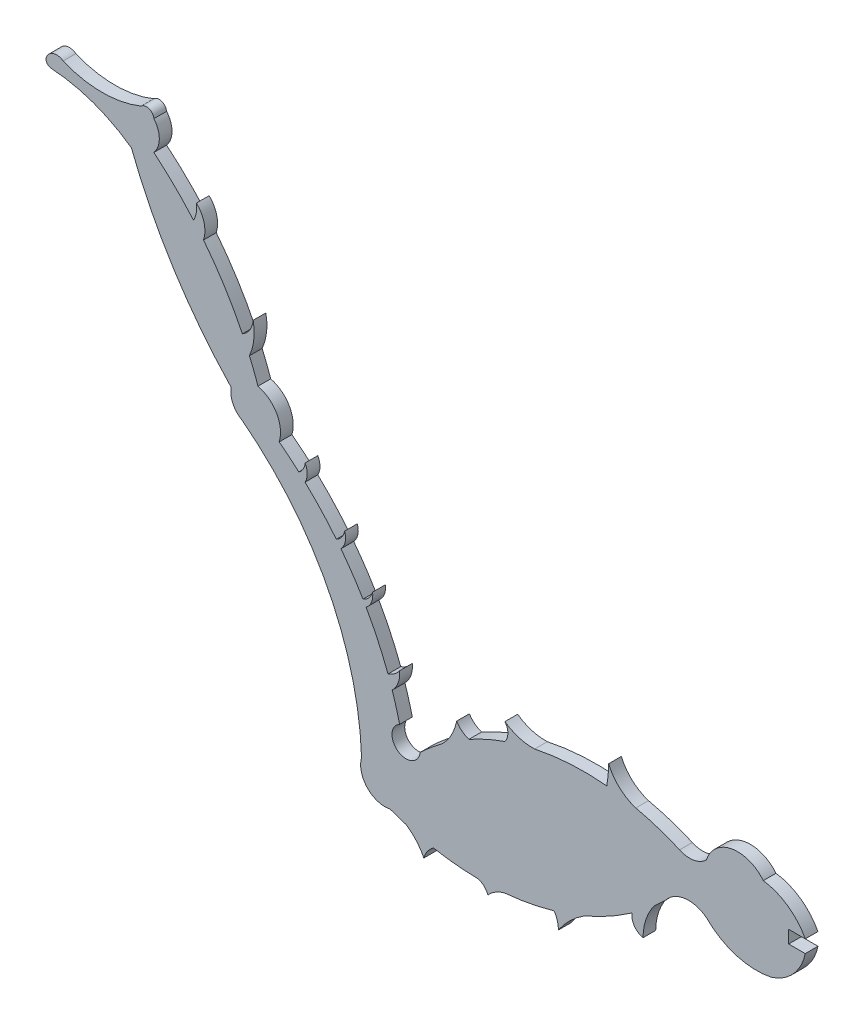
SolidWorks part; units mm, degrees
ref_plane "Front Plane" through (0, 0, 0) normal (0, 0, 1) x (1, 0, 0)
ref_plane "Top Plane" through (0, 0, 0) normal (0, 1, 0) x (1, 0, 0)
ref_plane "Right Plane" through (0, 0, 0) normal (1, 0, 0) x (0, 0, -1)
sketch "Sketch1" plane through (0, 0, 0) normal (0, 0, 1) x (1, 0, 0)
  line L0 (-80.679, -0.762) -> (-80.679, -1.524)
  line L1 (-80.679, -1.524) -> (-80.679, 0) construction
  line L2 (-80.679, -1.524) -> (-78.6924, -1.524)
  line L3 (-80.679, -0.762) -> (-80.679, 0)
  line L4 (-80.679, 0) -> (-78.6924, 0)
  arc A0 (-78.6924, -1.524) -> (-82.7841, -6.0206) centre (-84.5112, -0.339) cw
  arc A1 (-82.7841, -6.0206) -> (-90.5441, -3.7256) centre (-84.5475, 2.2837) cw
  arc A2 (-90.5441, -3.7256) -> (-95.4253, -4.3356) centre (-92.6791, -6.4758) ccw
  arc A3 (-95.4253, -4.3356) -> (-96.7733, -5.5862) centre (-117.5163, 18.1246) cw
  arc A4 (-128.4869, -11.4071) -> (-131.8923, -7.7736) centre (-129.1004, -8.5695) cw
  arc A5 (-78.6924, 0) -> (-83.7249, 3.5363) centre (-84.6733, -3.1623) ccw
  arc A6 (-83.7249, 3.5363) -> (-90.5441, 2.2837) centre (-86.7959, 1.0666) ccw
  arc A7 (-90.5441, 2.2837) -> (-93.7575, 1.7193) centre (-92.5453, 4.2476) cw
  arc A8 (-93.7575, 1.7193) -> (-99.0066, 3.4337) centre (-105.2112, -24.4568) ccw
  arc A9 (-124.8732, -3.7256) -> (-127.3296, -2.0395) centre (-126.5527, -3.54) cw
  arc A10 (-131.8923, -7.7736) -> (-146.1807, 20.0631) centre (-168.5324, -8.9952) ccw
  arc A11 (-127.3296, -2.0395) -> (-128.2185, 1.0666) centre (-165.7078, -11.3422) ccw
  arc A12 (-141.7677, 20.0631) -> (-144.3089, 24.581) centre (-145.1768, 21.1192) ccw
  arc A13 (-146.1807, 20.0631) -> (-147.5384, 22.8689) centre (-144.8885, 22.4199) cw
  arc A14 (-144.3089, 24.581) -> (-145.3362, 27.2331) centre (-183.0206, 11.111) ccw
  arc A15 (-147.5384, 22.8689) -> (-159.483, 41.7311) centre (-105.7936, 62.5171) cw
  arc A16 (-156.792, 42.6085) -> (-156.792, 46.1183) centre (-158.8327, 44.3634) ccw
  arc A17 (-156.792, 46.1183) -> (-158.3046, 46.6658) centre (-157.6814, 46.0244) ccw
  arc A18 (-158.3046, 46.6658) -> (-167.6721, 46.6658) centre (-162.9884, 58.009) cw
  arc A19 (-167.6721, 46.6658) -> (-169.6951, 46.0244) centre (-168.4487, 45.6042) ccw
  arc A20 (-169.6951, 46.0244) -> (-169.1239, 45.189) centre (-169.0841, 45.8292) ccw
  arc A21 (-169.1239, 45.189) -> (-159.483, 41.7311) centre (-170.2642, 26.841) cw
  arc A22 (-96.7733, -5.5862) -> (-98.1486, -9.6111) centre (-91.3669, -9.681) ccw
  arc A23 (-98.1486, -9.6111) -> (-99.4797, -7.7048) centre (-97.7605, -7.9222) cw
  arc A24 (-105.2112, -10.8764) -> (-108.3055, -13.8949) centre (-99.5218, -19.8037) ccw
  arc A25 (-108.3055, -13.8949) -> (-108.8071, -12.1512) centre (-111.1393, -13.7661) ccw
  arc A26 (-117.891, -13.3767) -> (-116.748, -14.4725) centre (-118.4141, -15.0663) cw
  arc A27 (-116.748, -14.4725) -> (-114.7038, -13.2532) centre (-113.7962, -17.0978) cw
  arc A28 (-126.5527, -12.0552) -> (-124.4286, -14.4725) centre (-129.9118, -17.1487) cw
  arc A29 (-124.4286, -14.4725) -> (-123.2679, -12.8495) centre (-121.6036, -15.2662) cw
  arc A30 (-126.5527, -12.0552) -> (-128.4869, -11.4071) centre (-117.5163, 18.1246) cw
  arc A31 (-117.891, -13.3767) -> (-123.2679, -12.8495) centre (-117.5163, 18.1246) cw
  arc A32 (-108.8071, -12.1512) -> (-114.7038, -13.2532) centre (-117.5163, 18.1246) cw
  arc A33 (-99.4797, -7.7048) -> (-105.2112, -10.8764) centre (-117.5163, 18.1246) cw
  arc A34 (-99.0066, 3.4337) -> (-102.2647, 6.4054) centre (-97.4243, 8.4403) cw
  arc A35 (-102.2647, 6.4054) -> (-102.4957, 3.9861) centre (-117.789, 6.6669) cw
  arc A36 (-111.1393, 3.4937) -> (-114.7038, 4.5609) centre (-111.3863, 9.1556) cw
  arc A37 (-114.7038, 4.5609) -> (-114.7038, 2.4925) centre (-116.0261, 3.5267) cw
  arc A38 (-122.2541, -1.524) -> (-120.4861, 1.7193) centre (-126.4669, 2.8761) ccw
  arc A39 (-120.4861, 1.7193) -> (-119.0262, 0.5536) centre (-118.1905, 3.0972) ccw
  arc A40 (-122.2541, -1.524) -> (-124.8732, -3.7256) centre (-105.2112, -24.4568) ccw
  arc A41 (-114.7038, 2.4925) -> (-119.0262, 0.5536) centre (-105.2112, -24.4568) ccw
  arc A42 (-102.4957, 3.9861) -> (-111.1393, 3.4937) centre (-105.2112, -24.4568) ccw
  arc A43 (-128.2185, 1.0666) -> (-127.3296, 3.5267) centre (-130.3726, 3.2356) ccw
  arc A44 (-127.3296, 3.5267) -> (-128.721, 2.4925) centre (-129.6671, 5.2184) cw
  arc A45 (-131.3478, 8.121) -> (-130.5762, 10.0643) centre (-132.5522, 9.7241) ccw
  arc A46 (-130.5762, 10.0643) -> (-131.7186, 8.7615) centre (-132.454, 10.5587) cw
  arc A47 (-134.3612, 12.6747) -> (-133.9261, 14.7258) centre (-135.8287, 14.0577) ccw
  arc A48 (-133.9261, 14.7258) -> (-134.9162, 13.3823) centre (-135.8328, 15.0944) cw
  arc A49 (-138.6669, 17.4365) -> (-138.6669, 19.4325) centre (-140.416, 18.4345) ccw
  arc A50 (-138.6669, 19.4325) -> (-139.4185, 18.1246) centre (-140.2935, 19.4973) cw
  arc A51 (-139.4185, 18.1246) -> (-141.7677, 20.0631) centre (-165.7078, -11.3422) ccw
  arc A52 (-134.9162, 13.3823) -> (-138.6669, 17.4365) centre (-165.7078, -11.3422) ccw
  arc A53 (-131.7186, 8.7615) -> (-134.3612, 12.6747) centre (-165.7078, -11.3422) ccw
  arc A54 (-128.721, 2.4925) -> (-131.3478, 8.121) centre (-165.7078, -11.3422) ccw
  arc A55 (-145.3362, 27.2331) -> (-144.8885, 31.1407) centre (-151.2542, 29.8907) ccw
  arc A56 (-144.8885, 31.1407) -> (-146.1807, 29.0791) centre (-147.4966, 31.3397) cw
  arc A57 (-150.8401, 36.497) -> (-151.6889, 39.913) centre (-153.9792, 37.5305) ccw
  arc A58 (-151.6889, 39.913) -> (-152.0407, 37.949) centre (-154.8593, 39.4674) cw
  arc A59 (-152.0407, 37.949) -> (-156.792, 42.6085) centre (-183.0206, 11.111) ccw
  arc A60 (-146.1807, 29.0791) -> (-150.8401, 36.497) centre (-183.0206, 11.111) ccw
extrude "Boss-Extrude1" add sketch "Sketch1" along normal blind 1.524
